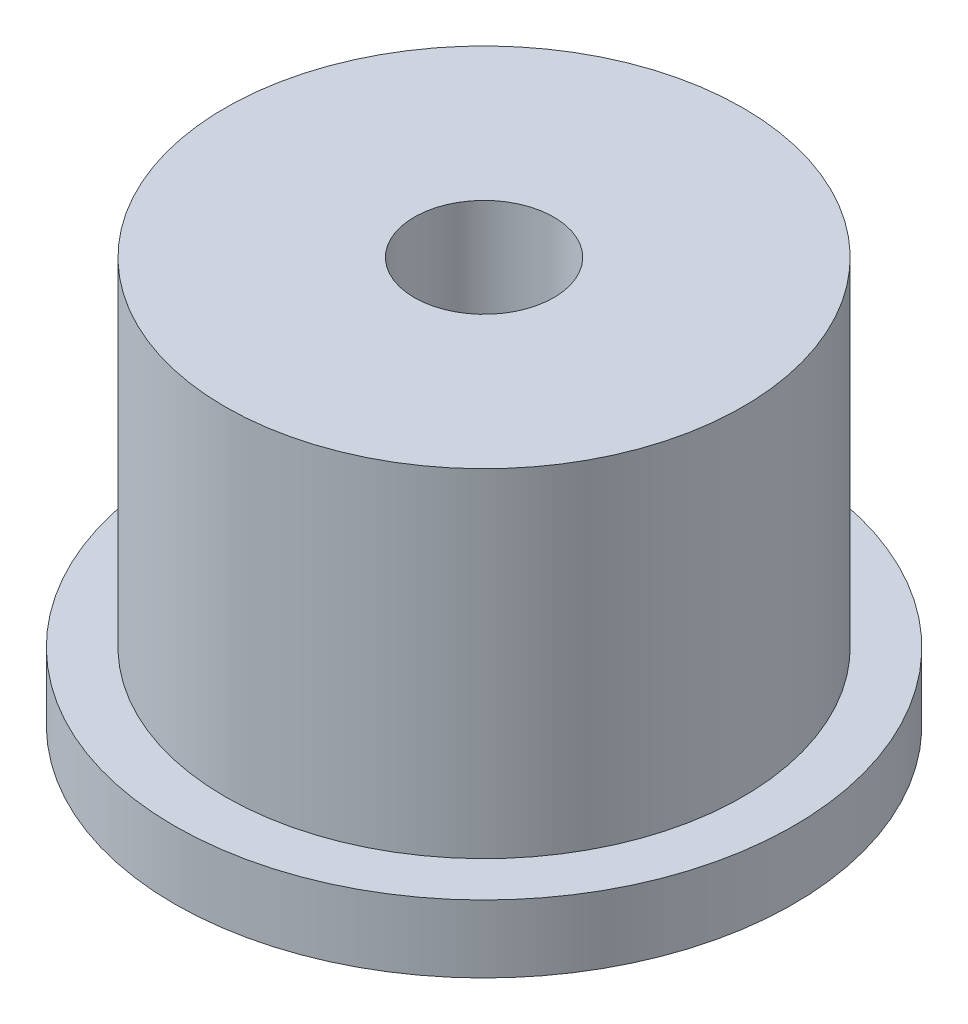
SolidWorks part; units mm, degrees
ref_plane "Front Plane" through (0, 0, 0) normal (0, 0, 1) x (1, 0, 0)
ref_plane "Top Plane" through (0, 0, 0) normal (0, 1, 0) x (1, 0, 0)
ref_plane "Right Plane" through (0, 0, 0) normal (1, 0, 0) x (0, 0, -1)
sketch "Sketch1" plane through (0, 0, 0) normal (0, 1, 0) x (1, 0, 0)
  circle A0 centre (0, 0) radius 13.75
  dimension "D1" = 27.5
extrude "Boss-Extrude1" add sketch "Sketch1" along normal blind 3
sketch "Sketch2" plane through (0, 3, 0) normal (0, 1, 0) x (1, 0, 0)
  circle A0 centre (0, 0) radius 11.5
  dimension "D1" = 23
extrude "Boss-Extrude2" add sketch "Sketch2" along normal blind 15
sketch "Sketch3" plane through (0, 18, 0) normal (0, 1, 0) x (1, 0, 0)
  circle A0 centre (0, 0) radius 3.1
  dimension "D1" = 6.2
extrude "Cut-Extrude1" cut sketch "Sketch3" against normal through all
